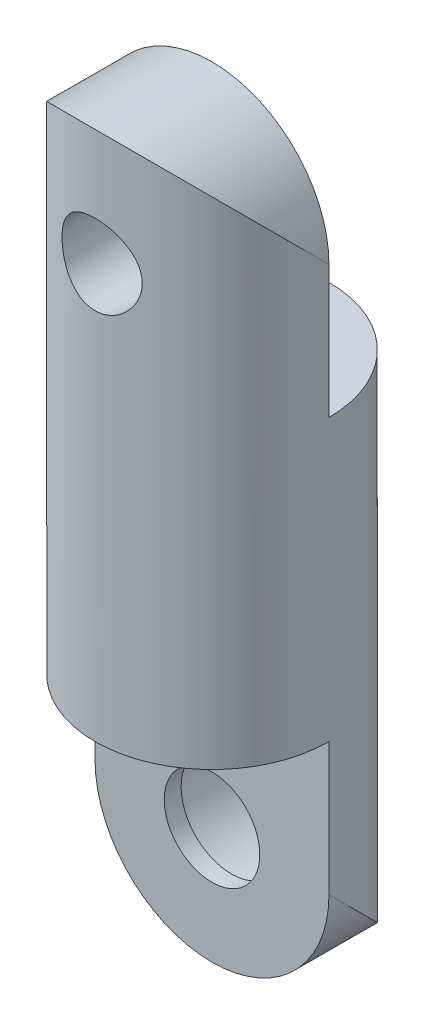
SolidWorks part; units mm, degrees
ref_plane "Front Plane" through (0, 0, 0) normal (0, 0, 1) x (1, 0, 0)
ref_plane "Top Plane" through (0, 0, 0) normal (0, 1, 0) x (1, 0, 0)
ref_plane "Right Plane" through (0, 0, 0) normal (1, 0, 0) x (0, 0, -1)
sketch "Croquis1" plane through (0, 0, 0) normal (0, 1, 0) x (1, 0, 0)
  circle A0 centre (0, 0) radius 9.525
  dimension "D1" = 19.05
extrude "Saliente-Extruir1" add sketch "Croquis1" along normal blind 63.5
sketch "Croquis2" plane through (0, 0, 0) normal (0, 0, 1) x (1, 0, 0)
  line L0 (9.525, 0) -> (9.525, 63.5) construction
  line L1 (-9.525, 63.5) -> (9.525, 63.5)
  line L2 (-9.525, 63.5) -> (-9.525, 43.18)
  line L3 (-9.525, 43.18) -> (9.525, 43.18)
  line L4 (9.525, 63.5) -> (9.525, 43.18)
  dimension "D1" = 20.32
extrude "Cortar-Extruir1" cut sketch "Croquis2" against normal blind 15.748
sketch "Croquis3" plane through (0, 0, 0) normal (0, 0, -1) x (-1, 0, 0)
  line L0 (9.525, 63.5) -> (9.525, 43.18) construction
  line L1 (-9.525, 63.5) -> (9.525, 63.5) construction
  line L2 (-9.525, 43.18) -> (-9.525, 63.5) construction
  line L3 (-16.6074, 53.975) -> (17.4952, 53.975) construction
  line L4 (-9.525, 53.975) -> (-9.525, 63.5)
  line L5 (-9.525, 63.5) -> (0, 63.5)
  line L6 (0, 63.5) -> (9.525, 63.5)
  line L7 (9.525, 63.5) -> (9.525, 53.975)
  arc A0 (9.525, 53.975) -> (-9.525, 53.975) centre (0, 53.975) ccw
  line M1 (9.525, 43.18) -> (9.525, 63.5)
  line M2 (9.525, 63.5) -> (-9.525, 63.5)
  line M3 (-9.525, 63.5) -> (-9.525, 43.18)
extrude "Cortar-Extruir2" cut sketch "Croquis3" against normal blind 15.748 contours A0 M2 M3 | A0 M1 M2
hole_wizard "Taladro roscado 5/16-181" positions "Croquis5" profile "Croquis4" tap size "5/16-18" standard "Ansi Inch"
sketch "Croquis5" plane through (0, 0, 0) normal (0, 0, -1) x (-1, 0, 0)
  point P0 (0, 53.975)
sketch "Croquis4" plane through (0, 53.975, 0) normal (1, 0, 0) x (0, 1, 0)
  line L0 (0, 0) -> (0, 24.8846)
  line L1 (0, 24.8846) -> (3.2639, 22.9235)
  line L2 (3.2639, 22.9235) -> (3.2639, 0)
  line L5 (3.2639, 0) -> (0, 0)
  line L10 (0, 24.8846) -> (-3.2639, 22.9235) construction
  line L11 (0, -6.35) -> (0, 107.95) construction
  dimension "Diámetro de perforador para roscar" = 6.5278
  dimension "Profundidad de perforador para roscar" = 22.9235
  dimension "Ángulo de perforador" = 118
cosmetic thread "Rosca de taladro1" parameters "D1"=9.525, "D2"=7.9375
sketch "Croquis6" plane through (0, 0, 0) normal (0, 0, 1) x (1, 0, 0)
  line L0 (9.525, 0) -> (9.525, 43.18) construction
  line L1 (-9.525, 0) -> (9.525, 0)
  line L2 (-9.525, 0) -> (-9.525, 20.32)
  line L3 (-9.525, 20.32) -> (9.525, 20.32)
  line L4 (9.525, 0) -> (9.525, 20.32)
  dimension "D1" = 20.32
extrude "Cortar-Extruir3" cut sketch "Croquis6" along normal blind 19.05
sketch "Croquis7" plane through (0, 0, 0) normal (0, 0, 1) x (1, 0, 0)
  line L0 (9.525, 0) -> (9.525, 20.32) construction
  line L1 (-9.525, 20.32) -> (-9.525, 0) construction
  line L2 (-22.0948, 9.525) -> (18.5589, 9.525) construction
  line L3 (-9.525, 9.525) -> (-9.525, 0)
  line L4 (-9.525, 0) -> (9.525, 0)
  line L5 (9.525, 0) -> (9.525, 9.525)
  arc A0 (-9.525, 9.525) -> (9.525, 9.525) centre (0, 9.525) ccw
  line M1 (-9.525, 20.32) -> (-9.525, 0)
  line M2 (-9.525, 0) -> (9.525, 0)
  line M3 (9.525, 0) -> (9.525, 20.32)
extrude "Cortar-Extruir4" cut sketch "Croquis7" against normal blind 19.05 contours A0 M1 M2 | A0 L4 M3
ref_plane "Plano1" through (0, 0, -9.525) normal (0, 0, -1) x (-1, 0, 0)
hole_wizard "Refrentado para tornillo con cabeza hueca de 5/161" positions "Croquis11" profile "Croquis10" counterbore size "5/16" standard "Ansi Inch"
sketch "Croquis11" plane through (0, 0, -9.525) normal (0, 0, -1) x (-1, 0, 0)
  point P0 (0, 9.525)
sketch "Croquis10" plane through (0, 9.525, -9.525) normal (1, 0, 0) x (0, 1, 0)
  line L0 (0, 0) -> (0, 11.8628)
  line L1 (0, 11.8628) -> (4.1021, 9.398)
  line L2 (4.1021, 9.398) -> (4.1021, 7.9375)
  line L3 (4.1021, 7.9375) -> (6.223, 7.9375)
  line L4 (6.223, 7.9375) -> (6.223, 0)
  line L5 (6.223, 0) -> (0, 0)
  line L10 (0, 11.8628) -> (-4.1021, 9.398) construction
  line L11 (0, -6.35) -> (0, 107.95) construction
  dimension "Diámetro de taladro" = 8.2042
  dimension "Profundidad de taladro" = 9.398
  dimension "Diámetro de refrentado" = 12.446
  dimension "Profundidad de refrentado" = 7.9375
  dimension "Ángulo de perforador" = 118
